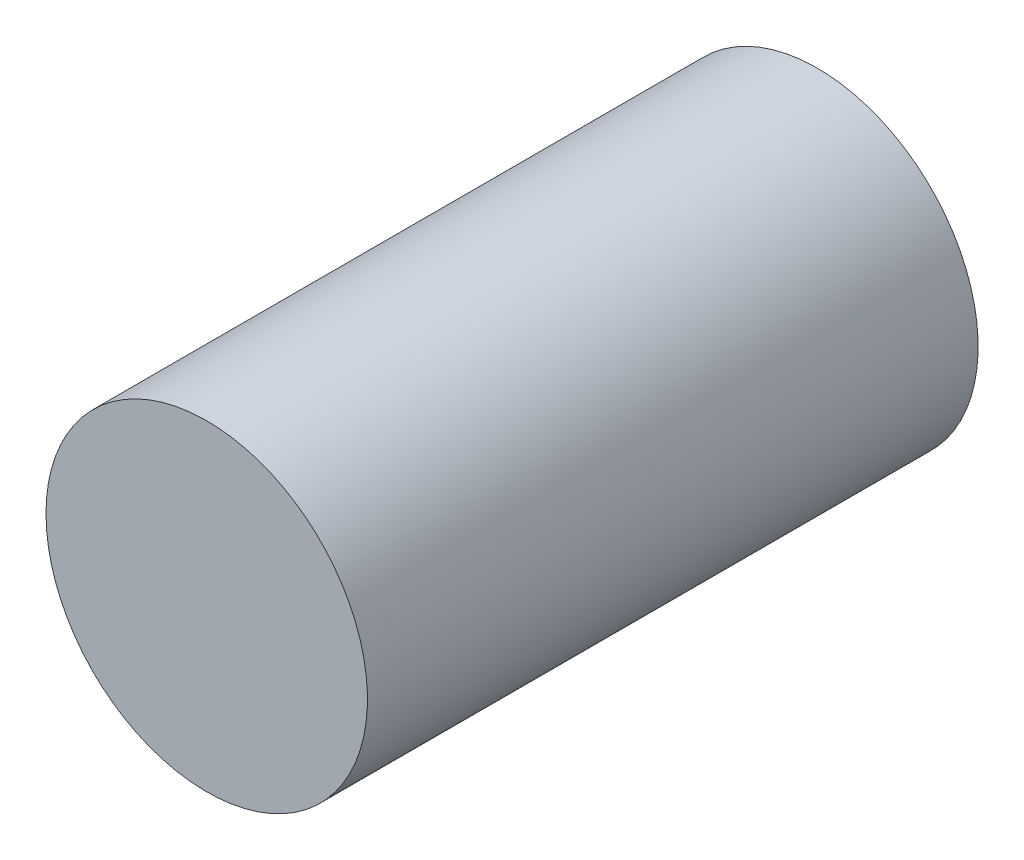
SolidWorks part; units mm, degrees
ref_plane "前视基准面" through (0, 0, 0) normal (0, 0, 1) x (1, 0, 0)
ref_plane "上视基准面" through (0, 0, 0) normal (0, 1, 0) x (1, 0, 0)
ref_plane "右视基准面" through (0, 0, 0) normal (1, 0, 0) x (0, 0, -1)
other "Configuration Table"
sketch "草图1" plane through (0, 0, 0) normal (0, 0, 1) x (1, 0, 0)
  circle A0 centre (0, 0) radius 1
extrude "凸台-拉伸2" add sketch "草图1" along normal blind 3.8
